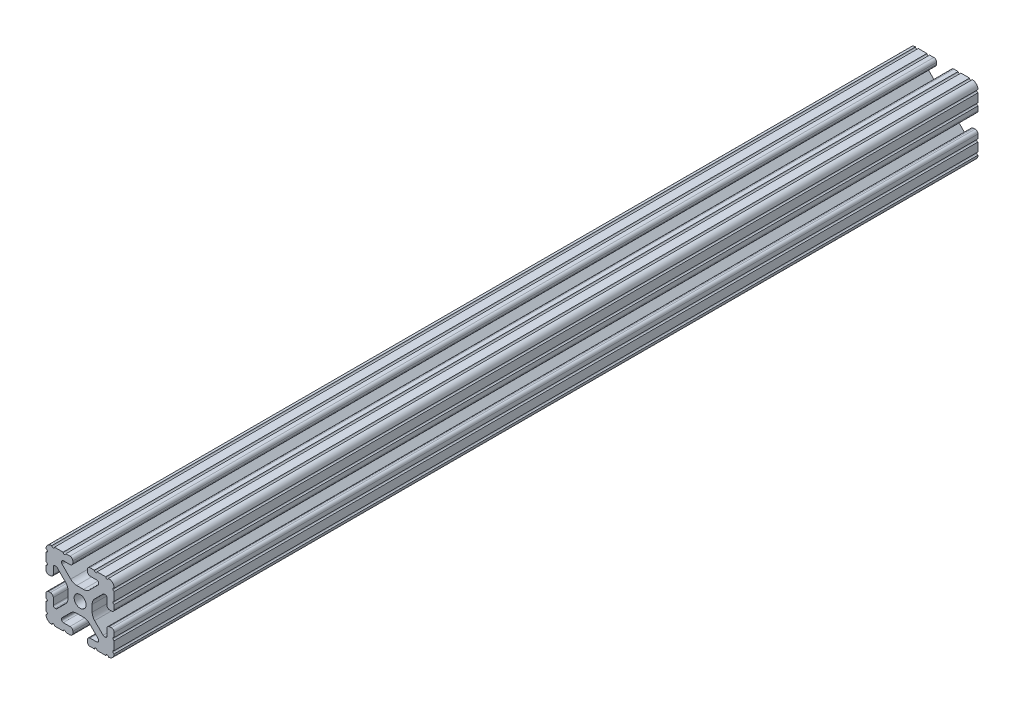
SolidWorks part; units mm, degrees
material "6105-T5 Aluminum"
ref_plane "Front Plane" through (0, 0, 0) normal (0, 0, 1) x (1, 0, 0)
ref_plane "Top Plane" through (0, 0, 0) normal (0, 1, 0) x (1, 0, 0)
ref_plane "Right Plane" through (0, 0, 0) normal (1, 0, 0) x (0, 0, -1)
sketch "Sketch1" plane through (0, 0, 0) normal (0, 0, 1) x (1, 0, 0)
  line L0 (-14.097, 10.287) -> (-13.5289, 10.287)
  line L1 (-12.9003, 10.0266) -> (-8.1292, 5.2555)
  line L2 (-6.738, 1.8969) -> (-6.738, -1.8969)
  line L3 (-8.1292, -5.2555) -> (-12.9003, -10.0266)
  line L4 (-13.5289, -10.287) -> (-14.097, -10.287)
  line L5 (-14.986, -9.398) -> (-14.986, -5.6388)
  line L6 (-16.5608, -4.064) -> (-17.4752, -4.064)
  line L7 (-19.05, -5.6388) -> (-19.05, -7.9756)
  line L8 (-19.05, -9.4996) -> (-19.05, -14.3256)
  line L9 (-19.05, -15.8496) -> (-19.05, -15.875)
  line L10 (-15.875, -19.05) -> (-15.8496, -19.05)
  line L11 (-14.3256, -19.05) -> (-9.4996, -19.05)
  line L12 (-7.9756, -19.05) -> (-5.6388, -19.05)
  line L13 (-4.064, -17.4752) -> (-4.064, -16.5608)
  line L14 (-5.6388, -14.986) -> (-9.398, -14.986)
  line L15 (-10.287, -14.097) -> (-10.287, -13.5289)
  line L16 (-10.0266, -12.9003) -> (-5.2555, -8.1292)
  line L17 (-1.8969, -6.738) -> (1.8969, -6.738)
  line L18 (5.2555, -8.1292) -> (10.0266, -12.9003)
  line L19 (10.287, -13.5289) -> (10.287, -14.097)
  line L20 (9.398, -14.986) -> (5.6388, -14.986)
  line L21 (4.064, -16.5608) -> (4.064, -17.4752)
  line L22 (5.6388, -19.05) -> (7.9756, -19.05)
  line L23 (9.4996, -19.05) -> (14.3256, -19.05)
  line L24 (15.8496, -19.05) -> (15.875, -19.05)
  line L25 (19.05, -15.875) -> (19.05, -15.8496)
  line L26 (19.05, -14.3256) -> (19.05, -9.4996)
  line L27 (19.05, -7.9756) -> (19.05, -5.6388)
  line L28 (17.4752, -4.064) -> (16.5608, -4.064)
  line L29 (14.986, -5.6388) -> (14.986, -9.398)
  line L30 (14.097, -10.287) -> (13.5289, -10.287)
  line L31 (12.9003, -10.0266) -> (8.1292, -5.2555)
  line L32 (6.738, -1.8969) -> (6.738, 1.8969)
  line L33 (8.1292, 5.2555) -> (12.9003, 10.0266)
  line L34 (13.5289, 10.287) -> (14.097, 10.287)
  line L35 (14.986, 9.398) -> (14.986, 5.6388)
  line L36 (16.5608, 4.064) -> (17.4752, 4.064)
  line L37 (19.05, 5.6388) -> (19.05, 7.9756)
  line L38 (19.05, 9.4996) -> (19.05, 14.3256)
  line L39 (19.05, 15.8496) -> (19.05, 15.875)
  line L40 (15.875, 19.05) -> (15.8496, 19.05)
  line L41 (14.3256, 19.05) -> (9.4996, 19.05)
  line L42 (7.9756, 19.05) -> (5.6388, 19.05)
  line L43 (4.064, 17.4752) -> (4.064, 16.5608)
  line L44 (5.6388, 14.986) -> (9.398, 14.986)
  line L45 (10.287, 14.097) -> (10.287, 13.5289)
  line L46 (10.0266, 12.9003) -> (5.2555, 8.1292)
  line L47 (1.8969, 6.738) -> (-1.8969, 6.738)
  line L48 (-5.2555, 8.1292) -> (-10.0266, 12.9003)
  line L49 (-10.287, 13.5289) -> (-10.287, 14.097)
  line L50 (-9.398, 14.986) -> (-5.6388, 14.986)
  line L51 (-4.064, 16.5608) -> (-4.064, 17.4752)
  line L52 (-5.6388, 19.05) -> (-7.9756, 19.05)
  line L53 (-9.4996, 19.05) -> (-14.3256, 19.05)
  line L54 (-15.8496, 19.05) -> (-15.875, 19.05)
  line L55 (-19.05, 15.875) -> (-19.05, 15.8496)
  line L56 (-19.05, 14.3256) -> (-19.05, 9.4996)
  line L57 (-19.05, 7.9756) -> (-19.05, 5.6388)
  line L58 (-17.4752, 4.064) -> (-16.5608, 4.064)
  line L59 (-14.986, 5.6388) -> (-14.986, 9.398)
  circle A0 centre (0, 0) radius 3.3274
  arc A1 (-14.097, 10.287) -> (-14.986, 9.398) centre (-14.097, 9.398) ccw
  arc A2 (-12.9003, 10.0266) -> (-13.5289, 10.287) centre (-13.5289, 9.398) ccw
  arc A3 (-6.738, 1.8969) -> (-8.1292, 5.2555) centre (-11.4878, 1.8969) ccw
  arc A4 (-8.1292, -5.2555) -> (-6.738, -1.8969) centre (-11.4878, -1.8969) ccw
  arc A5 (-13.5289, -10.287) -> (-12.9003, -10.0266) centre (-13.5289, -9.398) ccw
  arc A6 (-14.986, -9.398) -> (-14.097, -10.287) centre (-14.097, -9.398) ccw
  arc A7 (-14.986, -5.6388) -> (-16.5608, -4.064) centre (-16.5608, -5.6388) ccw
  arc A8 (-17.4752, -4.064) -> (-19.05, -5.6388) centre (-17.4752, -5.6388) ccw
  arc A9 (-19.05, -9.4996) -> (-19.05, -7.9756) centre (-19.05, -8.7376) ccw
  arc A10 (-19.05, -15.8496) -> (-19.05, -14.3256) centre (-19.05, -15.0876) ccw
  arc A11 (-19.05, -15.875) -> (-15.875, -19.05) centre (-15.875, -15.875) ccw
  arc A12 (-14.3256, -19.05) -> (-15.8496, -19.05) centre (-15.0876, -19.05) ccw
  arc A13 (-7.9756, -19.05) -> (-9.4996, -19.05) centre (-8.7376, -19.05) ccw
  arc A14 (-5.6388, -19.05) -> (-4.064, -17.4752) centre (-5.6388, -17.4752) ccw
  arc A15 (-4.064, -16.5608) -> (-5.6388, -14.986) centre (-5.6388, -16.5608) ccw
  arc A16 (-10.287, -14.097) -> (-9.398, -14.986) centre (-9.398, -14.097) ccw
  arc A17 (-10.0266, -12.9003) -> (-10.287, -13.5289) centre (-9.398, -13.5289) ccw
  arc A18 (-1.8969, -6.738) -> (-5.2555, -8.1292) centre (-1.8969, -11.4878) ccw
  arc A19 (5.2555, -8.1292) -> (1.8969, -6.738) centre (1.8969, -11.4878) ccw
  arc A20 (10.287, -13.5289) -> (10.0266, -12.9003) centre (9.398, -13.5289) ccw
  arc A21 (9.398, -14.986) -> (10.287, -14.097) centre (9.398, -14.097) ccw
  arc A22 (5.6388, -14.986) -> (4.064, -16.5608) centre (5.6388, -16.5608) ccw
  arc A23 (4.064, -17.4752) -> (5.6388, -19.05) centre (5.6388, -17.4752) ccw
  arc A24 (9.4996, -19.05) -> (7.9756, -19.05) centre (8.7376, -19.05) ccw
  arc A25 (15.8496, -19.05) -> (14.3256, -19.05) centre (15.0876, -19.05) ccw
  arc A26 (15.875, -19.05) -> (19.05, -15.875) centre (15.875, -15.875) ccw
  arc A27 (19.05, -14.3256) -> (19.05, -15.8496) centre (19.05, -15.0876) ccw
  arc A28 (19.05, -7.9756) -> (19.05, -9.4996) centre (19.05, -8.7376) ccw
  arc A29 (19.05, -5.6388) -> (17.4752, -4.064) centre (17.4752, -5.6388) ccw
  arc A30 (16.5608, -4.064) -> (14.986, -5.6388) centre (16.5608, -5.6388) ccw
  arc A31 (14.097, -10.287) -> (14.986, -9.398) centre (14.097, -9.398) ccw
  arc A32 (12.9003, -10.0266) -> (13.5289, -10.287) centre (13.5289, -9.398) ccw
  arc A33 (6.738, -1.8969) -> (8.1292, -5.2555) centre (11.4878, -1.8969) ccw
  arc A34 (8.1292, 5.2555) -> (6.738, 1.8969) centre (11.4878, 1.8969) ccw
  arc A35 (13.5289, 10.287) -> (12.9003, 10.0266) centre (13.5289, 9.398) ccw
  arc A36 (14.986, 9.398) -> (14.097, 10.287) centre (14.097, 9.398) ccw
  arc A37 (14.986, 5.6388) -> (16.5608, 4.064) centre (16.5608, 5.6388) ccw
  arc A38 (17.4752, 4.064) -> (19.05, 5.6388) centre (17.4752, 5.6388) ccw
  arc A39 (19.05, 9.4996) -> (19.05, 7.9756) centre (19.05, 8.7376) ccw
  arc A40 (19.05, 15.8496) -> (19.05, 14.3256) centre (19.05, 15.0876) ccw
  arc A41 (19.05, 15.875) -> (15.875, 19.05) centre (15.875, 15.875) ccw
  arc A42 (14.3256, 19.05) -> (15.8496, 19.05) centre (15.0876, 19.05) ccw
  arc A43 (7.9756, 19.05) -> (9.4996, 19.05) centre (8.7376, 19.05) ccw
  arc A44 (5.6388, 19.05) -> (4.064, 17.4752) centre (5.6388, 17.4752) ccw
  arc A45 (4.064, 16.5608) -> (5.6388, 14.986) centre (5.6388, 16.5608) ccw
  arc A46 (10.287, 14.097) -> (9.398, 14.986) centre (9.398, 14.097) ccw
  arc A47 (10.0266, 12.9003) -> (10.287, 13.5289) centre (9.398, 13.5289) ccw
  arc A48 (1.8969, 6.738) -> (5.2555, 8.1292) centre (1.8969, 11.4878) ccw
  arc A49 (-5.2555, 8.1292) -> (-1.8969, 6.738) centre (-1.8969, 11.4878) ccw
  arc A50 (-10.287, 13.5289) -> (-10.0266, 12.9003) centre (-9.398, 13.5289) ccw
  arc A51 (-9.398, 14.986) -> (-10.287, 14.097) centre (-9.398, 14.097) ccw
  arc A52 (-5.6388, 14.986) -> (-4.064, 16.5608) centre (-5.6388, 16.5608) ccw
  arc A53 (-4.064, 17.4752) -> (-5.6388, 19.05) centre (-5.6388, 17.4752) ccw
  arc A54 (-9.4996, 19.05) -> (-7.9756, 19.05) centre (-8.7376, 19.05) ccw
  arc A55 (-15.8496, 19.05) -> (-14.3256, 19.05) centre (-15.0876, 19.05) ccw
  arc A56 (-15.875, 19.05) -> (-19.05, 15.875) centre (-15.875, 15.875) ccw
  arc A57 (-19.05, 14.3256) -> (-19.05, 15.8496) centre (-19.05, 15.0876) ccw
  arc A58 (-19.05, 7.9756) -> (-19.05, 9.4996) centre (-19.05, 8.7376) ccw
  arc A59 (-19.05, 5.6388) -> (-17.4752, 4.064) centre (-17.4752, 5.6388) ccw
  arc A60 (-16.5608, 4.064) -> (-14.986, 5.6388) centre (-16.5608, 5.6388) ccw
extrude "Boss-Extrude1" add sketch "Sketch1" along normal blind 482.6
